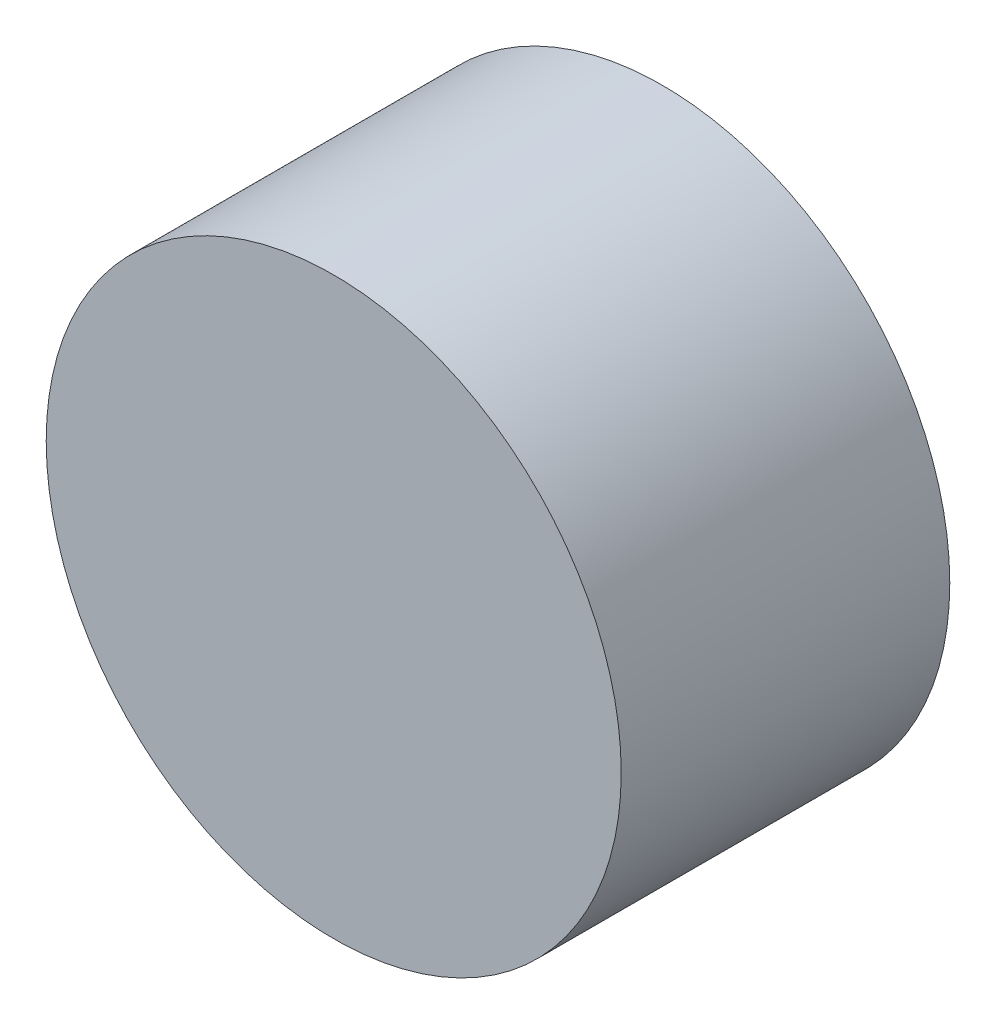
SolidWorks part; units mm, degrees
ref_plane "Front Plane" through (0, 0, 0) normal (0, 0, 1) x (1, 0, 0)
ref_plane "Top Plane" through (0, 0, 0) normal (0, 1, 0) x (1, 0, 0)
ref_plane "Right Plane" through (0, 0, 0) normal (1, 0, 0) x (0, 0, -1)
sketch "Sketch1" plane through (0, 0, 0) normal (0, 0, 1) x (1, 0, 0)
  circle A0 centre (0, 0) radius 5.5562
  dimension "D1" = 11.1125
extrude "Boss-Extrude1" add sketch "Sketch1" along normal blind 6.35
